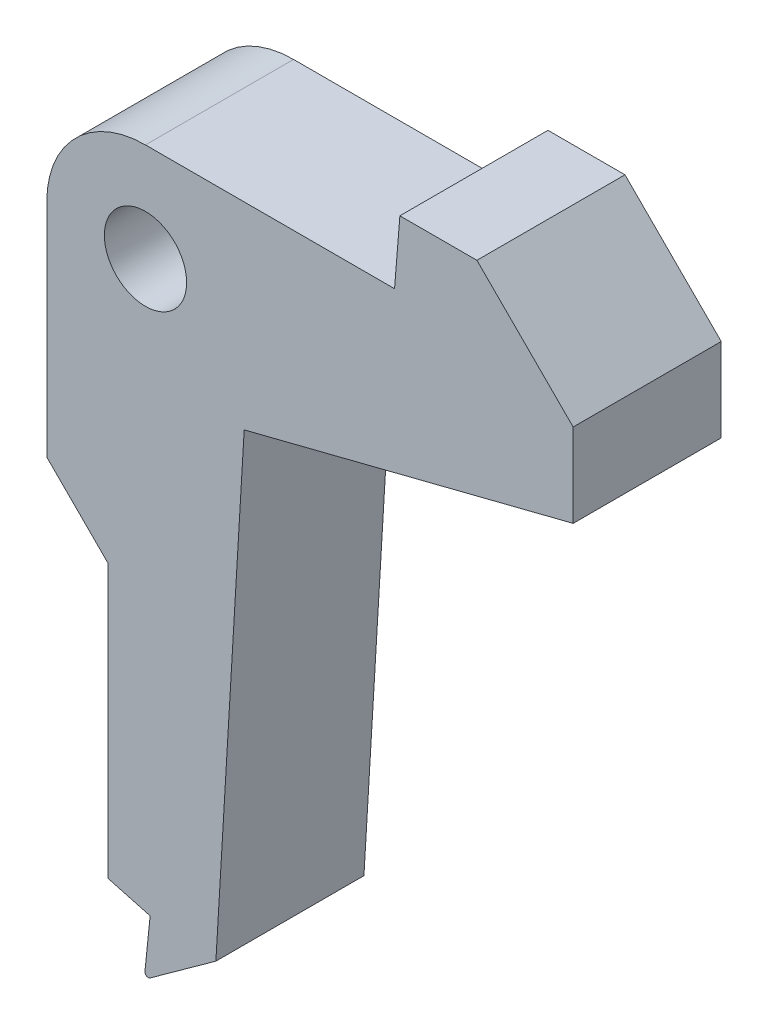
SolidWorks part; units mm, degrees
ref_plane "정면" through (0, 0, 0) normal (0, 0, 1) x (1, 0, 0)
ref_plane "윗면" through (0, 0, 0) normal (0, 1, 0) x (1, 0, 0)
ref_plane "우측면" through (0, 0, 0) normal (1, 0, 0) x (0, 0, -1)
sketch "스케치1" plane through (0, 0, 0) normal (0, 0, 1) x (1, 0, 0)
  line L0 (0, 6) -> (15.1382, 6)
  line L1 (15.1382, 6) -> (15.4624, 10)
  line L2 (15.4624, 10) -> (20.1449, 10)
  line L3 (20.1449, 10) -> (25.9953, 4.1497)
  line L4 (25.9953, 4.1497) -> (25.9953, -0.9252)
  line L6 (6, -6) -> (4.2784, -34.8282)
  line L7 (4.2784, -34.8282) -> (0.2827, -37.7084)
  line L8 (-0.0332, -37.5258) -> (0.2827, -34.4406)
  line L9 (0.2827, -34.4406) -> (-2.2721, -33.7477)
  line L10 (-2.2721, -33.7477) -> (-2.2721, -17.1612)
  line L11 (-2.2721, -17.1612) -> (-6, -13.4333)
  line L12 (-6, -13.4333) -> (-6, 0)
  line L13 (25.9953, -0.9252) -> (6, -6)
  circle A0 centre (0, 0) radius 2.5
  circle A1 centre (0, 0) radius 6
  arc A2 (0.2827, -37.7084) -> (-0.0332, -37.5258) centre (0.1657, -37.5462) cw
  dimension "D1" = 5
  dimension "D2" = 12
  dimension "D4" = 0.2
  dimension "D3" = 10
extrude "보스-돌출1" add sketch "스케치1" along normal blind 9
